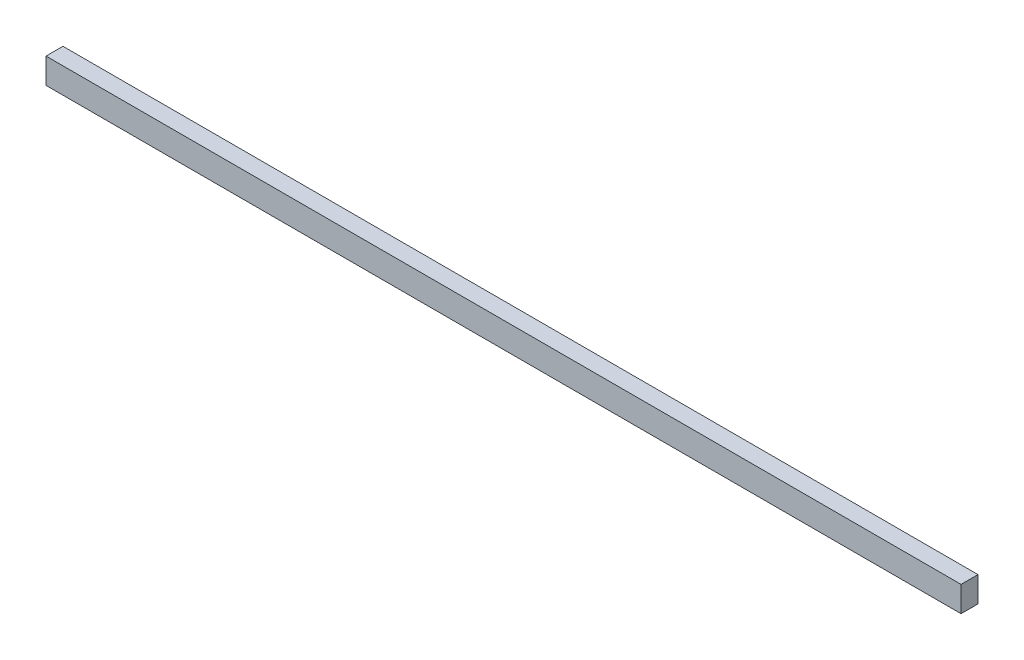
SolidWorks part; units mm, degrees
ref_plane "前视基准面" through (0, 0, 0) normal (0, 0, 1) x (1, 0, 0)
ref_plane "上视基准面" through (0, 0, 0) normal (0, 1, 0) x (1, 0, 0)
ref_plane "右视基准面" through (0, 0, 0) normal (1, 0, 0) x (0, 0, -1)
other "Configuration Table"
sketch "草图1" plane through (0, 0, 0) normal (0, 0, 1) x (1, 0, 0)
  line L1 (-540, -15) -> (540, -15)
  line L2 (-540, -15) -> (-540, 15)
  line L3 (-540, 15) -> (540, 15)
  line L4 (540, -15) -> (540, 15)
  line L5 (-540, -15) -> (540, 15) construction
  line L6 (-540, 15) -> (540, -15) construction
  point P0 (0, 0)
extrude "凸台-拉伸1" add sketch "草图1" along normal blind 20
